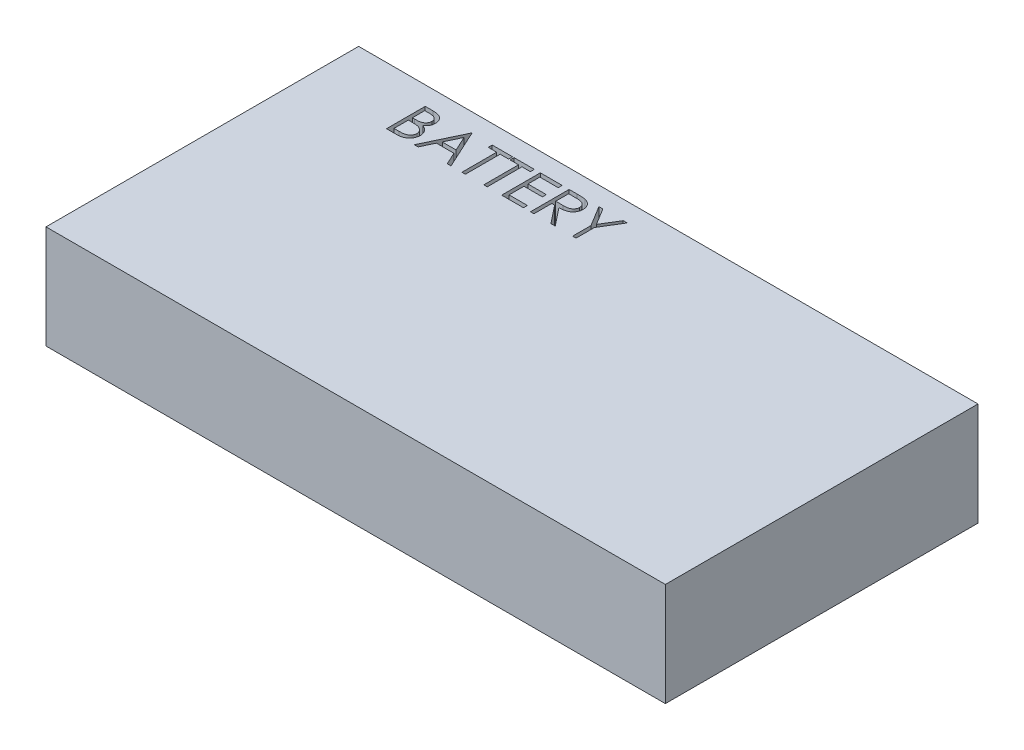
SolidWorks part; units mm, degrees
ref_plane "Front Plane" through (0, 0, 0) normal (0, 0, 1) x (1, 0, 0)
ref_plane "Top Plane" through (0, 0, 0) normal (0, 1, 0) x (1, 0, 0)
ref_plane "Right Plane" through (0, 0, 0) normal (1, 0, 0) x (0, 0, -1)
sketch "Sketch1" plane through (0, 0, 0) normal (0, 1, 0) x (1, 0, 0)
  line L1 (0, 0) -> (160.02, 0)
  line L2 (0, 0) -> (0, 80.772)
  line L3 (0, 80.772) -> (160.02, 80.772)
  line L4 (160.02, 0) -> (160.02, 80.772)
  dimension "D1" = 160.02
  dimension "D2" = 80.772
extrude "Boss-Extrude1" add sketch "Sketch1" along normal blind 26.67
sketch "Sketch2" plane through (0, 26.67, 0) normal (0, 1, 0) x (1, 0, 0)
  text T0 "BATTERY" font "Century Gothic" height 10
extrude "Cut-Extrude1" cut sketch "Sketch2" against normal blind 10
